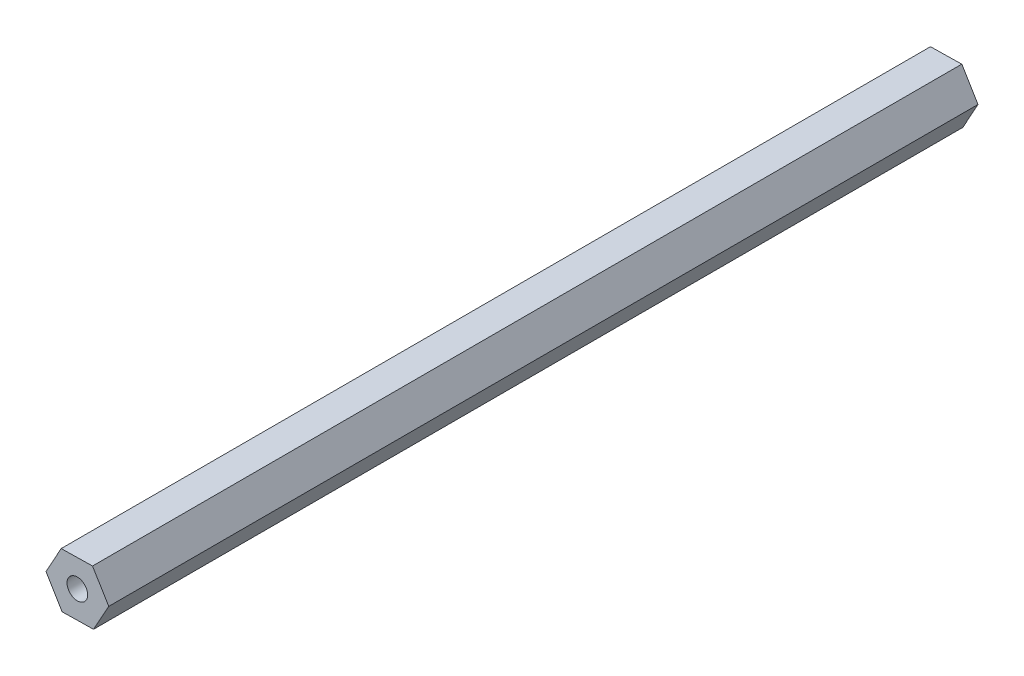
SolidWorks part; units mm, degrees
material "6061-T6 (SS)"
ref_plane "Front Plane" through (0, 0, 0) normal (0, 0, 1) x (1, 0, 0)
ref_plane "Top Plane" through (0, 0, 0) normal (0, 1, 0) x (1, 0, 0)
ref_plane "Right Plane" through (0, 0, 0) normal (1, 0, 0) x (0, 0, -1)
sketch "Sketch1" plane through (0, 0, 0) normal (0, 0, 1) x (1, 0, 0)
  line L1 (3.7846, -6.2802) -> (7.3311, 0.1374)
  line L2 (7.3311, 0.1374) -> (3.5465, 6.4176)
  line L3 (3.5465, 6.4176) -> (-3.7846, 6.2802)
  line L4 (-3.7846, 6.2802) -> (-7.3311, -0.1374)
  line L5 (-7.3311, -0.1374) -> (-3.5465, -6.4176)
  line L6 (-3.5465, -6.4176) -> (3.7846, -6.2802)
  circle A0 centre (0, 0) radius 6.35 construction
  circle A1 centre (0, 0) radius 2.413
  dimension "D2" = 4.826
  dimension "D1" = 12.7
extrude "Boss-Extrude1" add sketch "Sketch1" along normal blind 203.2
